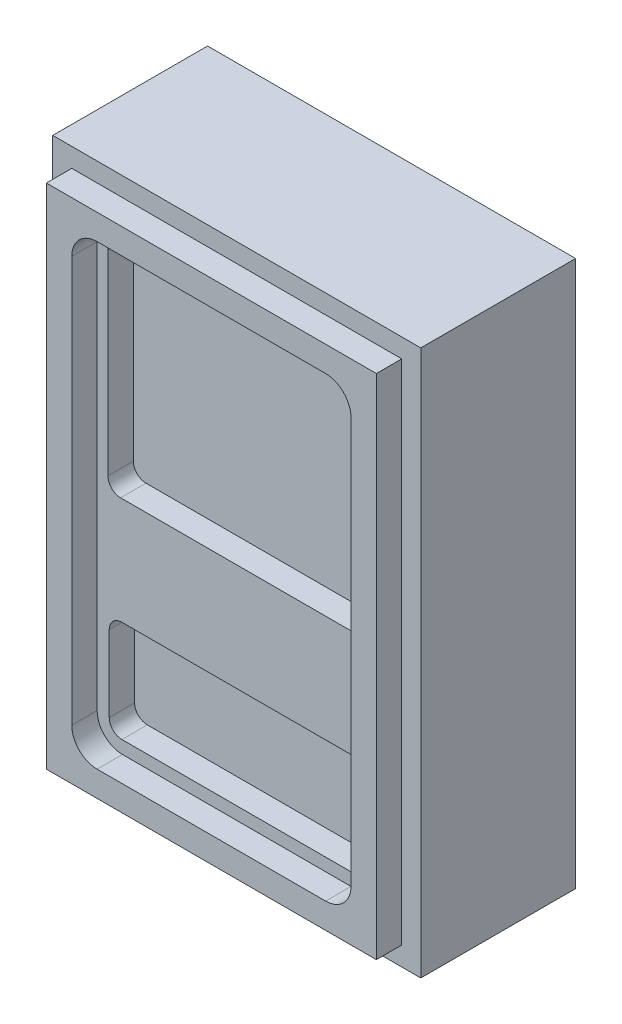
SolidWorks part; units mm, degrees
ref_plane "Plan de face" through (0, 0, 0) normal (0, 0, 1) x (1, 0, 0)
ref_plane "Plan de dessus" through (0, 0, 0) normal (0, 1, 0) x (1, 0, 0)
ref_plane "Plan de droite" through (0, 0, 0) normal (1, 0, 0) x (0, 0, -1)
sketch "Sketch1" plane through (0, 0, 0) normal (0, 0, 1) x (1, 0, 0)
  line L1 (-1.45, -2.15) -> (1.45, -2.15)
  line L2 (-1.45, -2.15) -> (-1.45, 2.15)
  line L3 (-1.45, 2.15) -> (1.45, 2.15)
  line L4 (1.45, -2.15) -> (1.45, 2.15)
  line L5 (-1.45, -2.15) -> (1.45, 2.15) construction
  line L6 (-1.45, 2.15) -> (1.45, -2.15) construction
  point P0 (0, 0)
  dimension "D1" = 2.9
  dimension "D2" = 4.3
extrude "Boss-Extrude1" add sketch "Sketch1" along normal blind 1.22
sketch "Sketch4" plane through (0, 0, 0) normal (0, 0, -1) x (-1, 0, 0)
  line L0 (0.65, 2) -> (0.65, 1.6)
  line L1 (-1.25, 2) -> (-0.65, 2)
  line L2 (-1.25, 2) -> (-1.25, 1.6)
  line L3 (-1.25, 1.6) -> (-0.65, 1.6)
  line L4 (-0.65, 2) -> (-0.65, 1.6)
  line L5 (-1.25, 2) -> (-0.65, 1.6) construction
  line L6 (-1.25, 1.6) -> (-0.65, 2) construction
  line L7 (0.65, 2) -> (1.25, 2)
  line L8 (1.25, 2) -> (1.25, 1.6)
  line L9 (0.65, 1.6) -> (1.25, 1.6)
  line L10 (0.65, 1.4) -> (0.65, 1)
  line L11 (0.65, 1.4) -> (1.25, 1.4)
  line L12 (1.25, 1.4) -> (1.25, 1)
  line L13 (0.65, 1) -> (1.25, 1)
  line L14 (0.65, 0.8) -> (0.65, 0.4)
  line L15 (0.65, 0.8) -> (1.25, 0.8)
  line L16 (1.25, 0.8) -> (1.25, 0.4)
  line L17 (0.65, 0.4) -> (1.25, 0.4)
  line L18 (0.65, 0.2) -> (0.65, -0.2)
  line L19 (0.65, 0.2) -> (1.25, 0.2)
  line L20 (1.25, 0.2) -> (1.25, -0.2)
  line L21 (0.65, -0.2) -> (1.25, -0.2)
  line L22 (0.65, -0.4) -> (0.65, -0.8)
  line L23 (0.65, -0.4) -> (1.25, -0.4)
  line L24 (1.25, -0.4) -> (1.25, -0.8)
  line L25 (0.65, -0.8) -> (1.25, -0.8)
  line L26 (0.65, -1) -> (0.65, -1.4)
  line L27 (0.65, -1) -> (1.25, -1)
  line L28 (1.25, -1) -> (1.25, -1.4)
  line L29 (0.65, -1.4) -> (1.25, -1.4)
  line L30 (0.65, -1.6) -> (0.65, -2)
  line L31 (0.65, -1.6) -> (1.25, -1.6)
  line L32 (1.25, -1.6) -> (1.25, -2)
  line L33 (0.65, -2) -> (1.25, -2)
  line L34 (-1.25, 1.4) -> (-1.25, 1)
  line L35 (-1.25, 1.4) -> (-0.65, 1.4)
  line L36 (-0.65, 1.4) -> (-0.65, 1)
  line L37 (-1.25, 1) -> (-0.65, 1)
  line L38 (-1.25, 0.8) -> (-1.25, 0.4)
  line L39 (-1.25, 0.8) -> (-0.65, 0.8)
  line L40 (-0.65, 0.8) -> (-0.65, 0.4)
  line L41 (-1.25, 0.4) -> (-0.65, 0.4)
  line L42 (-1.25, 0.2) -> (-1.25, -0.2)
  line L43 (-1.25, 0.2) -> (-0.65, 0.2)
  line L44 (-0.65, 0.2) -> (-0.65, -0.2)
  line L45 (-1.25, -0.2) -> (-0.65, -0.2)
  line L46 (-1.25, -0.4) -> (-1.25, -0.8)
  line L47 (-1.25, -0.4) -> (-0.65, -0.4)
  line L48 (-0.65, -0.4) -> (-0.65, -0.8)
  line L49 (-1.25, -0.8) -> (-0.65, -0.8)
  line L50 (-1.25, -1) -> (-1.25, -1.4)
  line L51 (-1.25, -1) -> (-0.65, -1)
  line L52 (-0.65, -1) -> (-0.65, -1.4)
  line L53 (-1.25, -1.4) -> (-0.65, -1.4)
  line L54 (-1.25, -1.6) -> (-1.25, -2)
  line L55 (-1.25, -1.6) -> (-0.65, -1.6)
  line L56 (-0.65, -1.6) -> (-0.65, -2)
  line L57 (-1.25, -2) -> (-0.65, -2)
  line L58 (-1.25, 2) -> (0.65, 2) construction
  line L59 (-1.25, 2) -> (-1.25, 1.4) construction
  line L60 (-0.65, 0) -> (0.65, 0) construction
  point P0 (-0.95, 1.8)
  point P62 (-0.7354, 1.998)
  dimension "D1" = 0.6
  dimension "D2" = 0.4
  dimension "D5" = 1.9
  dimension "D6" = 0.6
  dimension "D3" = 2
  dimension "D4" = 7
extrude "Boss-Extrude2" add sketch "Sketch4" along normal blind 0.08
sketch "Sketch3" plane through (0, 0, 1.22) normal (0, 0, 1) x (1, 0, 0)
  line L1 (-1.015, -0.0558) -> (1.015, -0.0558)
  line L2 (-1.015, -0.0558) -> (-1.015, 1.6842)
  line L3 (-1.015, 1.6842) -> (1.015, 1.6842)
  line L4 (1.015, -0.0558) -> (1.015, 1.6842)
  line L5 (-1.015, -0.0558) -> (1.015, 1.6842) construction
  line L6 (-1.015, 1.6842) -> (1.015, -0.0558) construction
  line L7 (-1.005, -1.7) -> (1.005, -1.7)
  line L8 (-1.005, -1.7) -> (-1.005, -0.9)
  line L9 (-1.005, -0.9) -> (1.005, -0.9)
  line L10 (1.005, -1.7) -> (1.005, -0.9)
  line L11 (-1.005, -1.7) -> (1.005, -0.9) construction
  line L12 (-1.005, -0.9) -> (1.005, -1.7) construction
  line L14 (1.45, 2.15) -> (-1.45, 2.15) construction
  line L15 (-1.45, -2.15) -> (1.45, -2.15) construction
  point P0 (0, 0.8142)
  point P5 (0, -1.3)
  point P10 (0, 0)
  dimension "D1" = 1.74
  dimension "D2" = 0.8
  dimension "D3" = 2.03
  dimension "D4" = 2.01
  dimension "D5" = 0.85
  dimension "D6" = 1.3358
extrude "Cut-Extrude2" cut sketch "Sketch3" against normal blind 0.2
fillet "Fillet1" radius 0.1 8 edges at (-1.005, -0.9, 1.12) (-1.005, -1.7, 1.12) (1.005, -1.7, 1.12) (1.005, -0.9, 1.12) (-1.015, -0.0558, 1.12) (1.015, -0.0558, 1.12) (1.015, 1.6842, 1.12) (-1.015, 1.6842, 1.12)
sketch "Sketch2" plane through (0, 0, 1.22) normal (0, 0, 1) x (1, 0, 0)
  line L0 (1.3, -2) -> (1.3, 2)
  line L1 (1.3, 2) -> (-1.3, 2)
  line L2 (-1.3, 2) -> (-1.3, -2)
  line L3 (-1.3, -2) -> (1.3, -2)
  line L4 (1.45, -2.15) -> (1.45, 2.15)
  line L5 (1.45, 2.15) -> (-1.45, 2.15)
  line L6 (-1.45, 2.15) -> (-1.45, -2.15)
  line L7 (-1.45, -2.15) -> (1.45, -2.15)
  line L8 (1.45, -2.15) -> (1.45, 2.15)
  line L9 (1.45, 2.15) -> (-1.45, 2.15)
  line L10 (-1.45, 2.15) -> (-1.45, -2.15)
  line L11 (-1.45, -2.15) -> (1.45, -2.15)
  line L12 (1.1, -1.8) -> (1.1, 1.8)
  line L13 (1.1, 1.8) -> (-1.1, 1.8)
  line L14 (-1.1, 1.8) -> (-1.1, -1.8)
  line L15 (-1.1, -1.8) -> (1.1, -1.8)
  dimension "D1" = 0
  dimension "D2" = 0.15
  dimension "D3" = 0.2
extrude "Boss-Extrude3" add sketch "Sketch2" along normal blind 0.2 contours L2 L3 L0 L1 L15 L14 L13 L12
fillet "Fillet2" radius 0.2 4 edges at (1.1, -1.8, 1.32) (1.1, 1.8, 1.32) (-1.1, -1.8, 1.32) (-1.1, 1.8, 1.32)
